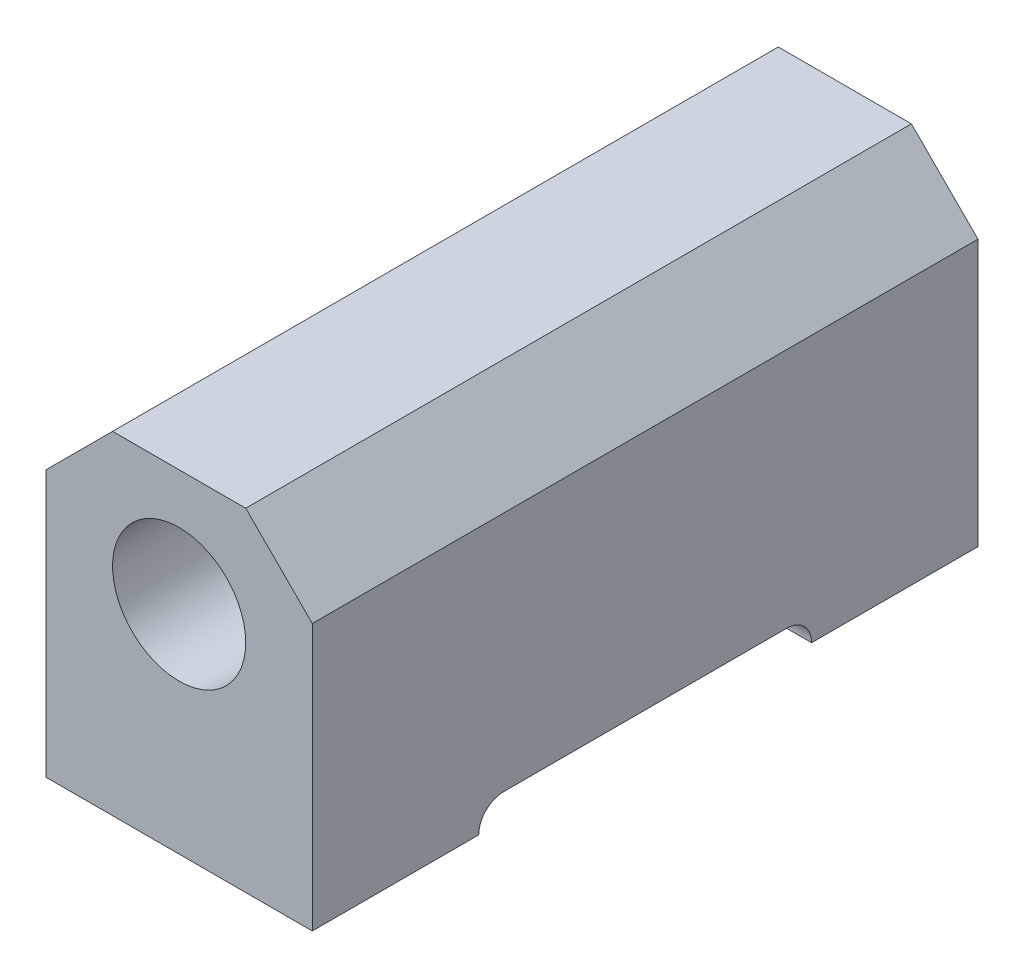
SolidWorks part; units mm, degrees
ref_plane "Plan de face" through (0, 0, 0) normal (0, 0, 1) x (1, 0, 0)
ref_plane "Plan de dessus" through (0, 0, 0) normal (0, 1, 0) x (1, 0, 0)
ref_plane "Plan de droite" through (0, 0, 0) normal (1, 0, 0) x (0, 0, -1)
sketch "Esquisse1" plane through (0, 0, 0) normal (0, 0, 1) x (1, 0, 0)
  line L0 (-16, 0) -> (16, 0)
  line L1 (16, 0) -> (16, 32)
  line L2 (16, 32) -> (8, 40)
  line L3 (8, 40) -> (-8, 40)
  line L4 (-8, 40) -> (-16, 32)
  line L5 (-16, 32) -> (-16, 0)
  line L6 (-26.6533, 32) -> (32.8789, 32) construction
  dimension "D1" = 32
  dimension "D2" = 16
  dimension "D3" = 40
  dimension "D4" = 135
  dimension "D5" = 16
extrude "Boss.-Extru.1" add sketch "Esquisse1" along normal blind 80
sketch "Esquisse2" plane through (16, 0, 0) normal (1, 0, 0) x (0, 0, -1)
  line L0 (-60, -3) -> (-60, 0)
  line L1 (-60, -3) -> (-20, -3)
  line L2 (-20, -3) -> (-20, 0)
  line L3 (-57, 3) -> (-23, 3)
  line L4 (-60, 0) -> (-13.4338, 0) construction
  line L5 (-80, 0) -> (0, 0) construction
  line L6 (-80, 0) -> (-80, 32) construction
  arc A0 (-60, 0) -> (-57, 3) centre (-57, 0) cw
  arc A1 (-20, 0) -> (-23, 3) centre (-23, 0) ccw
  dimension "D4" = 3
  dimension "D5" = 20
  dimension "D1" = 40
  dimension "D2" = 3
  dimension "D3" = 6
extrude "Enlèv. mat.-Extru.1" cut sketch "Esquisse2" against normal through all
hole_wizard "Dégagement M11" positions "Esquisse6" profile "Esquisse5" hole size "M1" standard "ISO"
sketch "Esquisse6" plane through (0, 0, 80) normal (0, 0, 1) x (1, 0, 0)
  line L0 (0, 0) -> (0, 38.5878) construction
  line L2 (-16, 0) -> (16, 0) construction
  point P0 (0, 26)
  dimension "D1" = 26
sketch "Esquisse5" plane through (0, 26, 80) normal (1, 0, 0) x (0, -1, 0)
  line L0 (0, 0) -> (0, 76.6188)
  line L1 (0, 76.6188) -> (8, 72)
  line L2 (8, 72) -> (8, 0)
  line L5 (8, 0) -> (0, 0)
  line L10 (0, 76.6188) -> (-8, 72) construction
  line L11 (0, -6.35) -> (0, 107.95) construction
  dimension "Diamètre du perçage" = 16
  dimension "Profondeur du perçage" = 72
  dimension "Angle de pointe" = 120
sketch "Esquisse3" plane through (0, 3, 0) normal (0, -1, 0) x (1, 0, 0)
  line L0 (16, 23) -> (16, 57) construction
  line L1 (-16, 80) -> (16, 80) construction
  circle A0 centre (0, 40) radius 5
  dimension "D1" = 10
  dimension "D2" = 16
  dimension "D3" = 40
extrude "Enlèv. mat.-Extru.2" cut sketch "Esquisse3" against normal up to next
sketch "Esquisse7" plane through (0, 0, 0) normal (0, -1, 0) x (1, 0, 0)
  line L0 (0, 0) -> (0, 12.9911) construction
  line L1 (-16, 0) -> (16, 0) construction
  circle A0 centre (0, 10) radius 2
  dimension "D1" = 4
  dimension "D2" = 10
extrude "Enlèv. mat.-Extru.3" cut sketch "Esquisse7" against normal up to next
